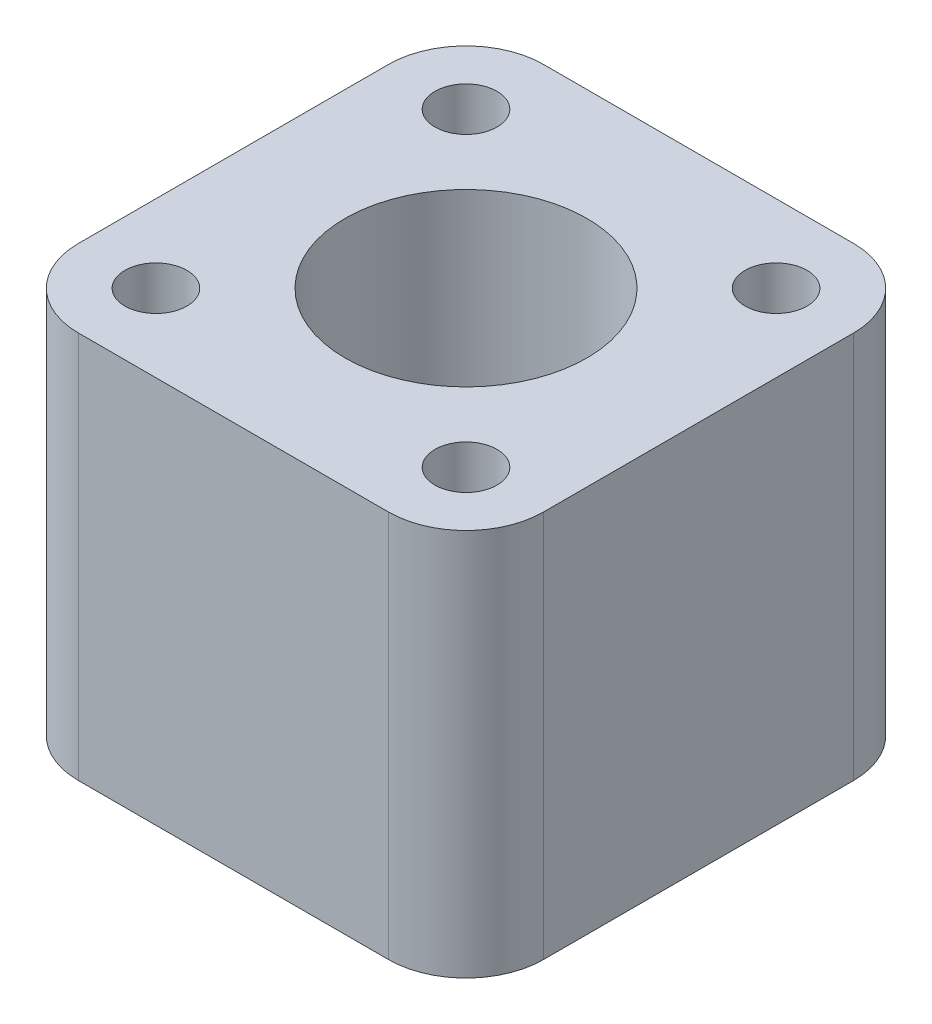
SolidWorks part; units mm, degrees
ref_plane "Front Plane" through (0, 0, 0) normal (0, 0, 1) x (1, 0, 0)
ref_plane "Top Plane" through (0, 0, 0) normal (0, 1, 0) x (1, 0, 0)
ref_plane "Right Plane" through (0, 0, 0) normal (1, 0, 0) x (0, 0, -1)
sketch "Sketch1" plane through (0, 0, 0) normal (0, 1, 0) x (1, 0, 0)
  line L1 (-6.35, -6.35) -> (6.35, -6.35) construction
  line L2 (-6.35, -6.35) -> (-6.35, 6.35) construction
  line L3 (-6.35, 6.35) -> (6.35, 6.35) construction
  line L4 (6.35, -6.35) -> (6.35, 6.35) construction
  line L5 (-6.35, -6.35) -> (6.35, 6.35) construction
  line L6 (-6.35, 6.35) -> (6.35, -6.35) construction
  line L7 (-9.525, -9.525) -> (9.525, -9.525)
  line L8 (-9.525, -9.525) -> (-9.525, 9.525)
  line L9 (-9.525, 9.525) -> (9.525, 9.525)
  line L10 (9.525, -9.525) -> (9.525, 9.525)
  line L11 (-9.525, -9.525) -> (9.525, 9.525) construction
  line L12 (-9.525, 9.525) -> (9.525, -9.525) construction
  circle A0 centre (-6.35, 6.35) radius 1.27
  circle A1 centre (6.35, 6.35) radius 1.27
  circle A2 centre (6.35, -6.35) radius 1.27
  circle A3 centre (-6.35, -6.35) radius 1.27
  circle A4 centre (0, 0) radius 3.9688
  point P0 (0, 0)
  point P6 (0, 0)
  dimension "D1" = 2.54
  dimension "D4" = 7.9375
  dimension "D2" = 19.05
  dimension "D3" = 12.7
extrude "Boss-Extrude1" add sketch "Sketch1" along normal blind 15.875
sketch "Sketch2" plane through (0, 15.875, 0) normal (0, 1, 0) x (1, 0, 0)
  circle A0 centre (0, 0) radius 4.9213
  circle A1 centre (0, 0) radius 5.715
  dimension "D1" = 9.8425
  dimension "D2" = 0.7937
extrude "Boss-Extrude2" [suppressed] add sketch "Sketch2" along normal blind 9.525
fillet "Fillet1" [suppressed] radius 0.7937
fillet "Fillet2" radius 3.175 4 edges at (9.525, 7.9375, -9.525) (-9.525, 7.9375, -9.525) (9.525, 7.9375, 9.525) (-9.525, 7.9375, 9.525)
sketch "Sketch3" plane through (0, 15.875, 0) normal (0, 1, 0) x (1, 0, 0)
  circle A0 centre (0, 0) radius 4.953
  dimension "D1" = 9.906
extrude "Cut-Extrude1" cut sketch "Sketch3" against normal blind 9.525
